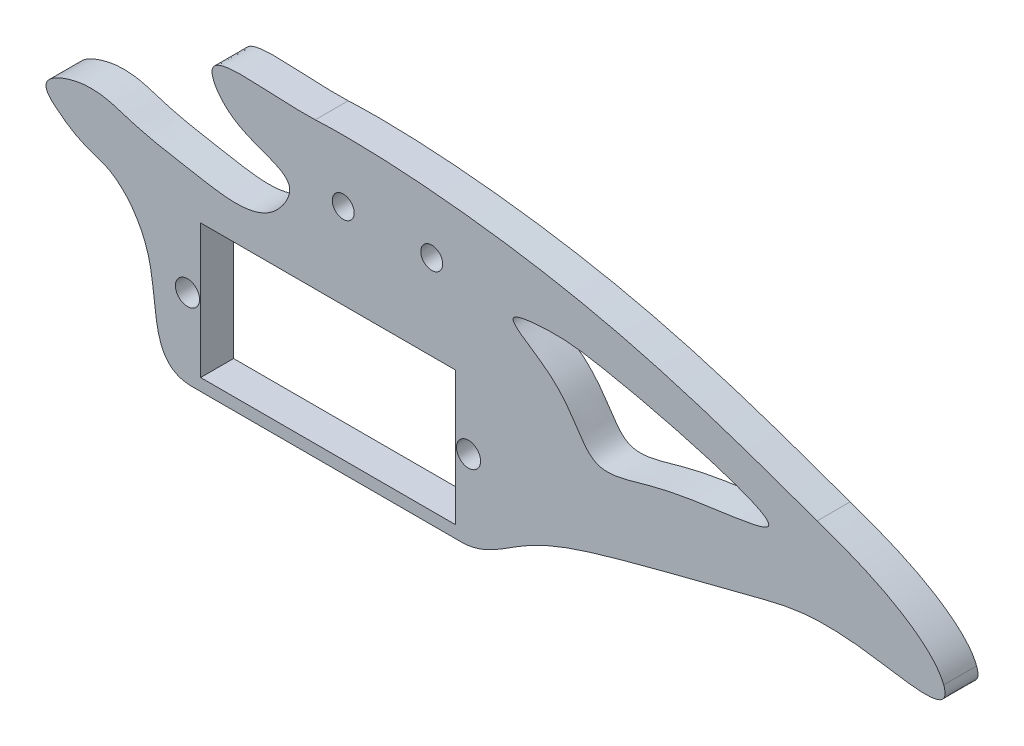
SolidWorks part; units mm, degrees
ref_plane "Front" through (0, 0, 0) normal (0, 0, 1) x (1, 0, 0)
ref_plane "Top" through (0, 0, 0) normal (0, 1, 0) x (1, 0, 0)
ref_plane "Right" through (0, 0, 0) normal (1, 0, 0) x (0, 0, -1)
sketch "Çizim1" plane through (0, 0, 0) normal (0, 0, 1) x (1, 0, 0)
  line L0 (-11.4978, 5.9601) -> (11.7022, 5.9601)
  line L1 (-11.4978, 5.9601) -> (-11.4978, -6.2399)
  line L2 (-11.4978, -6.2399) -> (11.7022, -6.2399)
  line L3 (11.7022, 5.9601) -> (11.7022, -6.2399)
  line L5 (12.2652, -7.3453) -> (-12.2353, -7.3453)
  circle A0 centre (-12.6978, -0.1399) radius 1.1
  circle A1 centre (12.9022, -0.0886) radius 1.1
  circle A2 centre (1.4921, 13.7349) radius 1
  circle A3 centre (9.5522, 13.7349) radius 1
  spline S0 degree 3 poles (22.1719, 9.5924) (23.6823, 3.5115) (31.3966, 6.8415) (46.2779, 7.2952) (31.2685, 11.5756) (24.7743, 12.9065) (21.0779, 13.5587) (15.2259, 12.81) (22.1719, 9.5924) (23.6823, 3.5115) (31.3966, 6.8415) knots -0.262534 -0.212784 -0.124174 0 0.114687 0.313852 0.537606 0.626374 0.737466 0.787216 0.875826 1 1.114687 1.313852 1.537606 only from (24.5652, 5.0248) to (24.5652, 5.0248)
  spline S1 degree 3 poles (44.6646, 10.5329) (34.6117, 14.1809) (22.9474, 18.0857) (3.9072, 19.5459) (-1.0552, 19.3156) knots 0 0 0 0 0.663075 0.975069 0.975069 0.975069 0.975069
  spline S2 degree 3 poles (-1.0552, 19.3156) (-1.8895, 19.2769) (-5.4019, 19.3477) (-11.8339, 19.852) (-8.3137, 14.3074) (-2.022, 14.1709) (-5.6384, 8.3137) (-11.65, 9.5803) (-17.3554, 10.4574) (-21.4748, 12.1971) (-26.2148, 10.4061) (-25.4266, 9.1147) (-24.8463, 8.6142) knots 0 0 0 0 0.070362 0.155384 0.208377 0.311744 0.352432 0.476858 0.569052 0.643479 0.705244 0.743354 0.743354 0.743354 0.743354
  spline S3 degree 3 poles (-12.2353, -7.3453) (-16.2145, -7.3453) (-14.6618, 0.5583) (-19.7454, 6.8689) (-22.4373, 6.5365) (-24.8463, 8.6142) knots 0 0 0 0 0.437166 0.729739 1 1 1 1
  spline S4 degree 3 poles (12.2652, -7.3453) (14.2904, -7.3453) (18.2041, -4.1477) (26.7333, -1.3079) (38.5435, 1.4451) (45.644, 3.6154) (57.0991, 0.9357) (56.1831, 3.358) knots 0 0 0 0 0.131307 0.304515 0.607289 0.857345 1 1 1 1
  spline S6 degree 3 poles (44.6646, 10.5329) (46.4981, 9.8675) (51.2724, 8.2252) (55.5954, 4.9122) (56.1831, 3.358) knots 0 0 0 0 0.546915 1 1 1 1
  point P0 (0.1022, -0.1399)
  point P1 (0.1022, -0.1399)
  dimension "D3" = 2.2
  dimension "D4" = 2.2
  dimension "D5" = 2
  dimension "D7" = 2
  dimension "D1" = 23.2
  dimension "D2" = 12.2
  dimension "D6" = 1.2
extrude "Yükseklik-Ekstrüzyon1" add sketch "Çizim1" along normal blind 3
